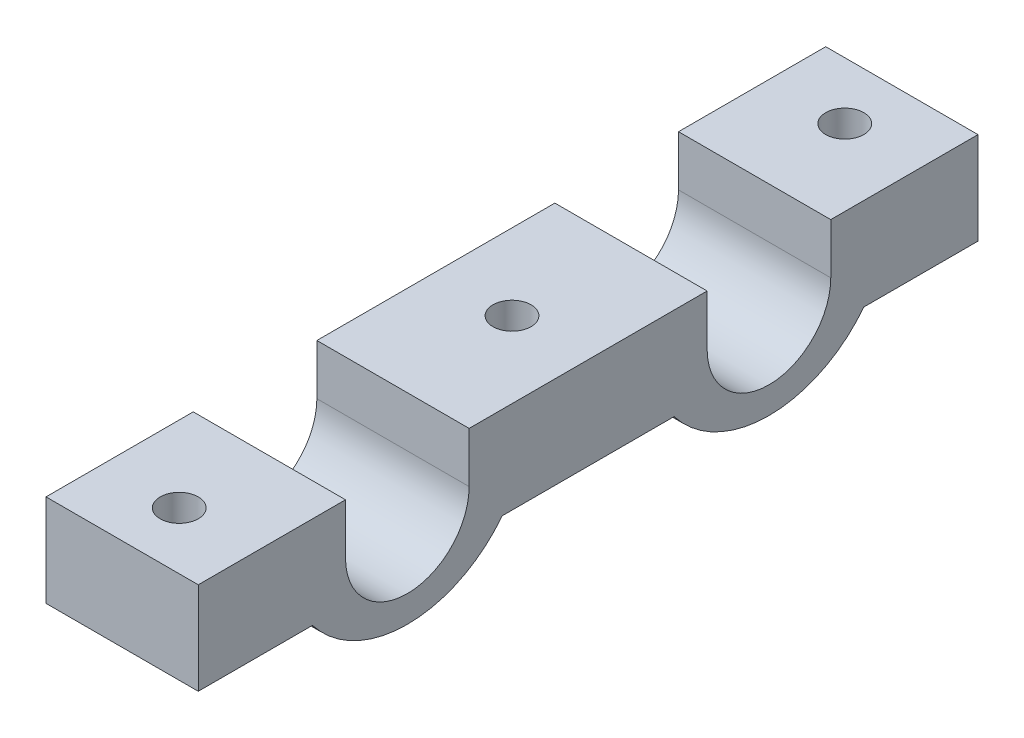
SolidWorks part; units mm, degrees
ref_plane "Front Plane" through (0, 0, 0) normal (0, 0, 1) x (1, 0, 0)
ref_plane "Top Plane" through (0, 0, 0) normal (0, 1, 0) x (1, 0, 0)
ref_plane "Right Plane" through (0, 0, 0) normal (1, 0, 0) x (0, 0, -1)
sketch "Sketch2" plane through (0, 0, 0) normal (1, 0, 0) x (0, 0, -1)
  line L0 (-15.24, 0) -> (15.24, 0) construction
  line L1 (-16.24, 0) -> (-54.9202, 0) construction
  line L2 (16.24, 0) -> (78.76, 0) construction
  line L3 (0, 0) -> (95, 0) construction
  line L4 (111.24, 0) -> (149.9202, 0) construction
  line L5 (-24.9202, -11) -> (-54.9202, -11)
  line L6 (24.9202, -11) -> (70.0798, -11)
  line L7 (119.9202, -11) -> (149.9202, -11)
  line L8 (-54.9202, 0) -> (-54.9202, -11)
  line L9 (149.9202, 0) -> (149.9202, -11)
  line L10 (-54.9202, 0) -> (-54.9202, 13.24)
  line L11 (-54.9202, 13.24) -> (-16.24, 13.24)
  line L12 (-16.24, 13.24) -> (-16.24, 0)
  line L13 (16.24, 0) -> (16.24, 13.24)
  line L14 (16.24, 13.24) -> (78.76, 13.24)
  line L15 (78.76, 13.24) -> (78.76, 0)
  line L16 (111.24, 0) -> (111.24, 13.24)
  line L17 (111.24, 13.24) -> (149.9202, 13.24)
  line L18 (149.9202, 13.24) -> (149.9202, 0)
  line L19 (0, -16.24) -> (0, -23.24) construction
  arc A0 (-15.24, 0) -> (15.24, 0) centre (0, 0) ccw construction
  arc A1 (-16.24, 0) -> (16.24, 0) centre (0, 0) ccw
  arc A2 (79.76, 0) -> (110.24, 0) centre (95, 0) ccw construction
  arc A3 (78.76, 0) -> (111.24, 0) centre (95, 0) ccw
  arc A6 (-24.9202, -11) -> (24.9202, -11) centre (0, 0) ccw construction
  arc A7 (70.0798, -11) -> (119.9202, -11) centre (95, 0) ccw construction
  arc A8 (-24.9202, -11) -> (24.9202, -11) centre (0, 8.2484) ccw
  arc A9 (70.0798, -11) -> (119.9202, -11) centre (95, 8.2484) ccw
  dimension "D6" = 11
  dimension "D11" = 7
  dimension "D1" = 30.48
  dimension "D3" = 95
  dimension "D5" = 30
  dimension "D7" = 11
  dimension "D8" = 11
  dimension "D9" = 13.24
  dimension "D10" = 204.8404
  dimension "D2" = 1
  dimension "D4" = 1
extrude "Boss-Extrude1" add sketch "Sketch2" along normal blind 40
sketch "Sketch3" plane through (0, 13.24, 0) normal (0, 1, 0) x (1, 0, 0)
  line L0 (0, -54.9202) -> (0, -24.9202) construction
  line L1 (0, -54.9202) -> (0, -24.9202) construction
  line L3 (40, -54.9202) -> (0, -54.9202) construction
  line L5 (40, 78.76) -> (40, 16.24) construction
  line L8 (40, -54.9202) -> (0, -54.9202) construction
  line L9 (40, -16.24) -> (40, -54.9202) construction
  line L10 (0, 78.76) -> (0, 16.24) construction
  line L11 (40, 16.24) -> (0, 16.24) construction
  line L16 (40, 16.24) -> (0, 16.24) construction
  line L18 (40, 78.76) -> (40, 16.24) construction
  line L19 (0, 78.76) -> (0, 16.24) construction
  line L24 (0, 47.5) -> (40, 47.5) construction
  line L25 (40, 78.76) -> (0, 78.76) construction
  circle A0 centre (20, -39.9202) radius 5
  circle A1 centre (20, 134.9202) radius 5
  circle A2 centre (20, 47.5) radius 5
  point P6 (0, -39.9202)
  point P14 (20, -54.9202)
  dimension "D1" = 10
extrude "Cut-Extrude1" cut sketch "Sketch3" against normal up to next
